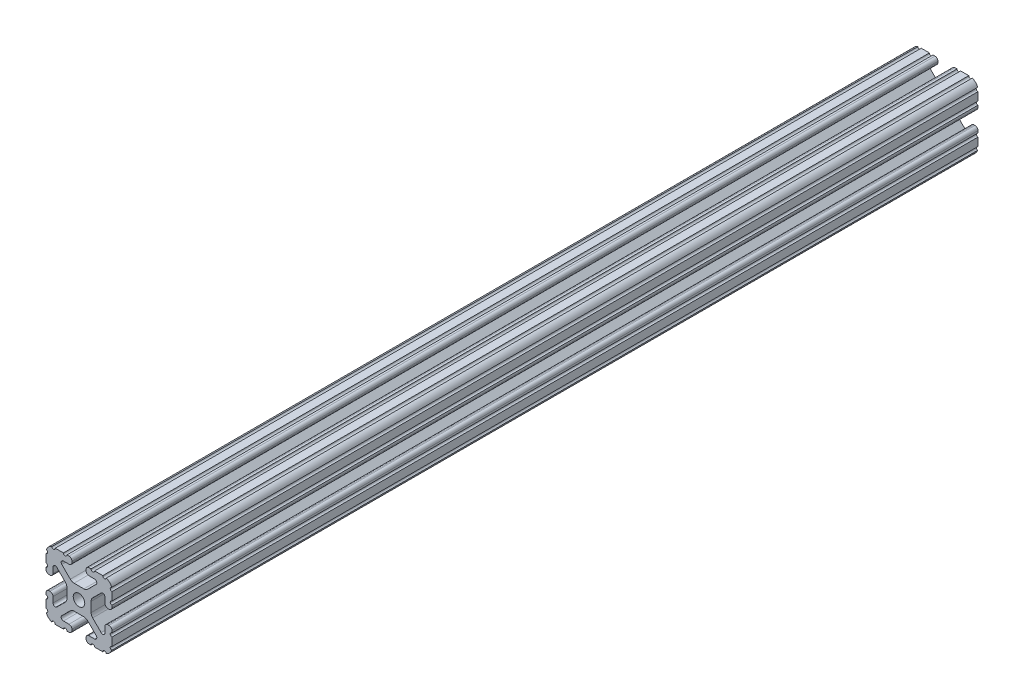
SolidWorks part; units mm, degrees
ref_plane "Front Plane" through (0, 0, 0) normal (0, 0, 1) x (1, 0, 0)
ref_plane "Top Plane" through (0, 0, 0) normal (0, 1, 0) x (1, 0, 0)
ref_plane "Right Plane" through (0, 0, 0) normal (1, 0, 0) x (0, 0, -1)
sketch "Sketch2" plane through (0, 0, 0) normal (0, 0, 1) x (1, 0, 0)
  line L0 (0, 19.05) -> (0, -19.05) construction
  line L1 (-19.05, 0) -> (19.05, 0) construction
  line L2 (4.064, -19.05) -> (19.05, -19.05)
  line L3 (19.05, -19.05) -> (19.05, -4.064)
  line L4 (4.064, -19.05) -> (4.064, -14.986)
  line L5 (4.064, -14.986) -> (12.1123, -14.986)
  line L6 (12.1123, -14.986) -> (4.1113, -6.985)
  line L7 (0, 0) -> (19.05, -19.05) construction
  line L8 (19.05, -4.064) -> (14.986, -4.064)
  line L9 (14.986, -4.064) -> (14.986, -12.1123)
  line L10 (14.986, -12.1123) -> (6.985, -4.1113)
  circle A0 centre (0, 0) radius 3.3274
  arc A1 (8.9963, -14.986) -> (9.909, -12.7826) centre (8.9963, -13.6953) ccw construction
  point P8 (0, -6.985)
  dimension "Center Hole Diameter" = 6.6548
  dimension "Rail Height" = 38.1
  dimension "Rail Width" = 38.1
  dimension "T-Slot Width" = 8.128
  dimension "Slot Inner Width" = 20.574
  dimension "Thickness" = 4.064
  dimension "Slot Depth" = 8.001
  dimension "D1" = 4.064
sketch "Sketch3" plane through (0, 0, 0) normal (1, 0, 0) x (0, 0, -1)
  line L0 (-250, -19.05) -> (250, -19.05) construction
  line L1 (-224.6, 0) -> (224.6, 0) construction
  dimension "Length" = 500
  dimension "D1" = 25.4
sketch "Sketch4" plane through (0, 0, 0) normal (0, 0, 1) x (1, 0, 0)
  line L0 (5.7912, -19.05) -> (14.3002, -19.05)
  line L1 (4.064, -19.05) -> (19.05, -19.05) construction
  line L2 (4.064, -19.05) -> (4.064, -14.986) construction
  line L3 (4.064, -14.986) -> (12.1123, -14.986) construction
  line L4 (4.064, -16.7132) -> (4.064, -17.3228)
  line L5 (5.7912, -14.986) -> (8.9963, -14.986)
  line L6 (0, -6.985) -> (2.833, -6.985)
  line L7 (12.1123, -14.986) -> (4.1113, -6.985) construction
  line L8 (5.0152, -7.8889) -> (9.909, -12.7826)
  line L9 (19.05, -19.05) -> (19.05, -4.064) construction
  line L10 (14.986, -12.1123) -> (6.985, -4.1113) construction
  line L11 (14.986, -4.064) -> (14.986, -12.1123) construction
  line L12 (14.986, -8.9963) -> (14.986, -5.7912)
  line L13 (19.05, -4.064) -> (14.986, -4.064) construction
  line L14 (16.7132, -4.064) -> (17.3228, -4.064)
  line L15 (19.05, -5.7912) -> (19.05, -14.3002)
  line L16 (12.7826, -9.909) -> (7.8889, -5.0152)
  line L17 (6.985, 0) -> (6.985, -2.833)
  line L18 (-19.05, 0) -> (19.05, 0) construction
  line L19 (0, -6.985) -> (0, -3.3274)
  line L20 (0, 19.05) -> (0, -19.05) construction
  line L21 (6.985, 0) -> (3.3274, 0)
  arc A0 (4.064, -17.3228) -> (5.7912, -19.05) centre (5.7912, -17.3228) ccw
  arc A2 (4.064, -16.7132) -> (5.7912, -14.986) centre (5.7912, -16.7132) cw
  arc A3 (8.9963, -14.986) -> (9.909, -12.7826) centre (8.9963, -13.6953) ccw
  arc A4 (2.833, -6.985) -> (5.0152, -7.8889) centre (2.833, -10.0711) cw
  arc A5 (14.3002, -19.05) -> (19.05, -14.3002) centre (14.3002, -14.3002) ccw
  arc A6 (12.7826, -9.909) -> (14.986, -8.9963) centre (13.6953, -8.9963) ccw
  arc A7 (14.986, -5.7912) -> (16.7132, -4.064) centre (16.7132, -5.7912) cw
  arc A8 (17.3228, -4.064) -> (19.05, -5.7912) centre (17.3228, -5.7912) cw
  arc A9 (7.8889, -5.0152) -> (6.985, -2.833) centre (10.0711, -2.833) cw
  circle A10 centre (0, 0) radius 3.3274 construction
  arc A11 (0, -3.3274) -> (3.3274, 0) centre (0, 0) ccw
  dimension "D1" = 4.7498
  dimension "D2" = 3.0861
  dimension "D3" = 1.7272
extrude "Boss-Extrude1" add sketch "Sketch4" along normal mid plane 500
sketch "Sketch5" plane through (0, 0, 0) normal (0, 0, 1) x (1, 0, 0)
  line L0 (4.064, -19.05) -> (19.05, -19.05) construction
  line L1 (5.7912, -14.986) -> (8.9963, -14.986) construction
  line L3 (0, 0) -> (19.05, -19.05) construction
  line L4 (8.9963, -14.986) -> (8.9963, -19.05) construction
  line L5 (12.1123, -14.986) -> (4.1113, -6.985) construction
  circle A0 centre (14.7395, -19.05) radius 1.016
  circle A1 centre (7.9803, -19.05) radius 1.016
  circle A2 centre (19.05, -14.7395) radius 1.016
  circle A3 centre (19.05, -7.9803) radius 1.016
  point P10 (7.3938, -14.986)
  point P12 (13.6953, -8.9963)
  dimension "D1" = 2.032
extrude "Cut-Extrude1" cut sketch "Sketch5" against normal through all both and the other way through all
mirror "Mirror1" about plane through (0, 0, 0) normal (1, 0, 0) of bodies 137 134
mirror "Mirror2" about plane through (0, 0, 0) normal (0, 1, 0) of bodies 135
equation "\"D1@Boss-Extrude1\"=\"Length@Sketch3\""
equation "\"D1@Sketch2\"=\"Thickness@Sketch2\""
equation "\"D2@Sketch4\"=\"Slot Inner Width@Sketch2\"*0.15"
equation "\"D1@Sketch4\"=\"D3@Sketch4\"*2.75"
equation "\"D3@Sketch4\"=\"Thickness@Sketch2\"*0.425"
equation "\"D1@Sketch5\"=\"Thickness@Sketch2\"*0.5"
